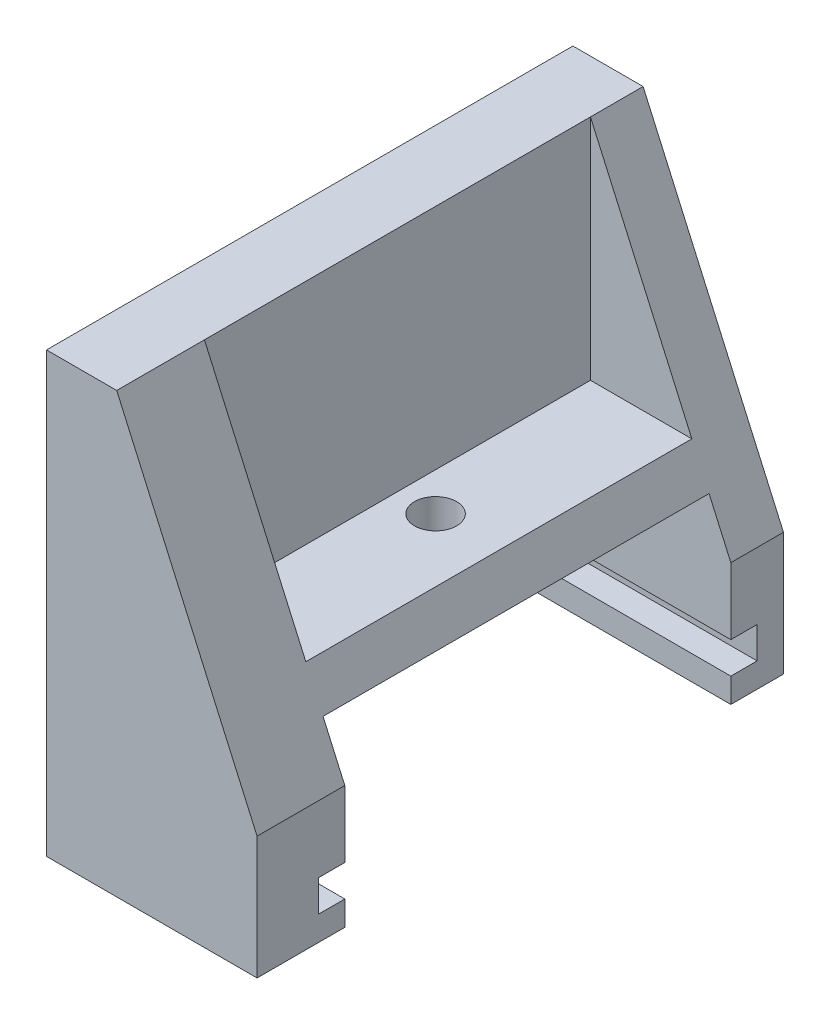
SolidWorks part; units mm, degrees
ref_plane "Front Plane" through (0, 0, 0) normal (0, 0, 1) x (1, 0, 0)
ref_plane "Top Plane" through (0, 0, 0) normal (0, 1, 0) x (1, 0, 0)
ref_plane "Right Plane" through (0, 0, 0) normal (1, 0, 0) x (0, 0, -1)
sketch "Sketch1" plane through (0, 0, 0) normal (0, 0, 1) x (1, 0, 0)
  line L0 (0, 0) -> (0, -25)
  line L1 (0, -25) -> (12, -25)
  line L2 (12, -25) -> (12, -18)
  line L3 (12, -18) -> (4, 0)
  line L4 (4, 0) -> (0, 0)
  dimension "D1" = 25
  dimension "D2" = 12
  dimension "D3" = 7
  dimension "D4" = 4
extrude "Boss-Extrude1" add sketch "Sketch1" against normal blind 30
sketch "Sketch4" plane through (0, 0, 0) normal (-1, 0, 0) x (0, 0, 1)
  line L0 (-30, 0) -> (-30, -25) construction
  line L1 (-27, -15.208) -> (-5, -15.208)
  line L2 (-27, -15.208) -> (-27, -25.208)
  line L3 (-27, -25.208) -> (-5, -25.208)
  line L4 (-5, -15.208) -> (-5, -25.208)
  point P4 (-27, -20.208)
  dimension "D1" = 22
  dimension "D2" = 10
  dimension "D3" = 3
extrude "Cut-Extrude2" cut sketch "Sketch4" against normal blind 15 contours L2 L1 L4 L3
sketch "Sketch5" plane through (0, 0, 0) normal (-1, 0, 0) x (0, 0, 1)
  line L0 (-5, -15.208) -> (-5, -25) construction
  line L1 (-5, -21.8) -> (-3.5, -21.8)
  line L2 (-5, -21.8) -> (-5, -23.6)
  line L3 (-5, -23.6) -> (-3.5, -23.6)
  line L4 (-3.5, -21.8) -> (-3.5, -23.6)
  line L5 (-5, -25) -> (0, -25) construction
  dimension "D1" = 1.8
  dimension "D2" = 1.5
  dimension "D3" = 1.4
extrude "Cut-Extrude3" cut sketch "Sketch5" against normal blind 15
ref_plane "Plane1" through (0, 0, -16) normal (0, 0, 1) x (1, 0, 0)
mirror "Mirror1" about plane through (0, 0, -16) normal (0, 0, 1) of "Cut-Extrude3"
sketch "Sketch6" plane through (0, 0, -16) normal (0, 0, 1) x (1, 0, 0)
  line L0 (4, 0) -> (4, -13)
  line L1 (4, -13) -> (9.7778, -13)
  line L2 (12, -18) -> (4, 0) construction
  line L3 (9.7778, -13) -> (4, 0)
  dimension "D1" = 13
extrude "Cut-Extrude4" cut sketch "Sketch6" against normal mid plane 22
sketch "Sketch7" plane through (0, -13, 0) normal (0, 1, 0) x (1, 0, 0)
  line L0 (-6.6, 16) -> (6.6, 16) construction
  circle A0 centre (6.1728, 16) radius 1.2
  dimension "D1" = 2.4
extrude "Cut-Extrude5" cut sketch "Sketch7" against normal blind 4 contours A0
